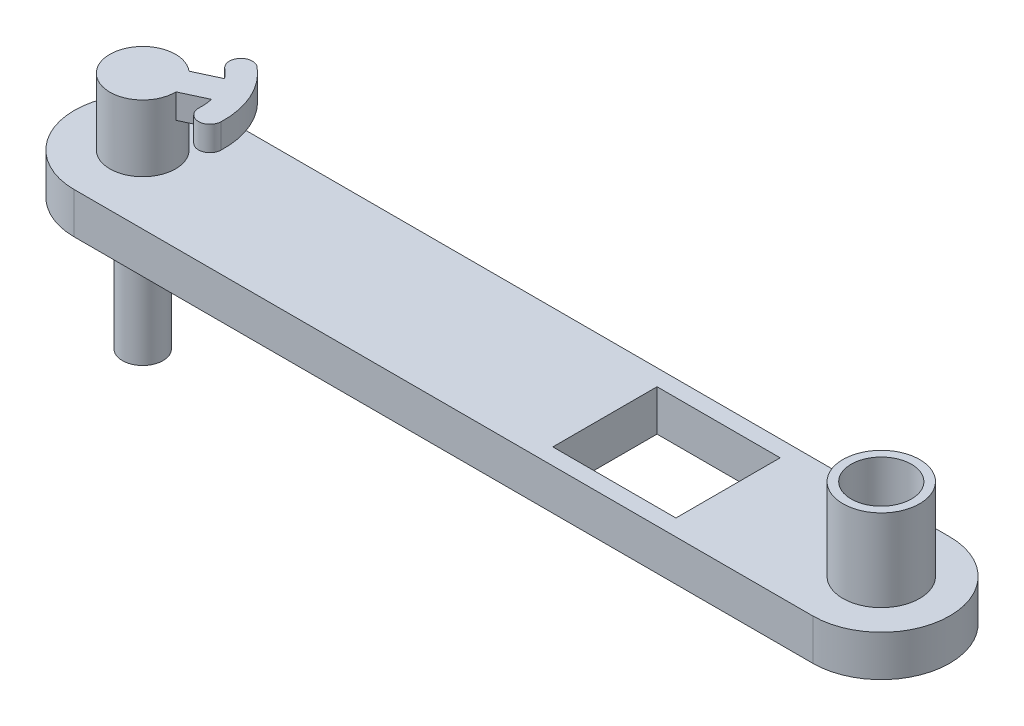
SolidWorks part; units mm, degrees
ref_plane "Front Plane" through (0, 0, 0) normal (0, 0, 1) x (1, 0, 0)
ref_plane "Top Plane" through (0, 0, 0) normal (0, 1, 0) x (1, 0, 0)
ref_plane "Right Plane" through (0, 0, 0) normal (1, 0, 0) x (0, 0, -1)
sketch "Sketch1" plane through (0, 0, 0) normal (0, 1, 0) x (1, 0, 0)
  line L0 (0, 0) -> (90, 0) construction
  line L1 (0, 8.35) -> (90, 8.35)
  line L2 (0, -8.35) -> (90, -8.35)
  arc A0 (0, 8.35) -> (0, -8.35) centre (0, 0) ccw
  arc A1 (90, -8.35) -> (90, 8.35) centre (90, 0) ccw
  point P3 (45, 0)
extrude "corps" add sketch "Sketch1" along normal blind 5
sketch "Esquisse1" plane through (0, 0, 0) normal (0, -1, 0) x (1, 0, 0)
  circle A0 centre (0, 0) radius 2.475
  dimension "D1" = 4.95
extrude "pulley hold" add sketch "Esquisse1" along normal blind 16
sketch "Esquisse2" plane through (0, 5, 0) normal (0, 1, 0) x (1, 0, 0)
  circle A0 centre (0, 0) radius 4
extrude "knob hold" add sketch "Esquisse2" along normal blind 8.1
sketch "Esquisse4" plane through (0, 5, 0) normal (0, 1, 0) x (1, 0, 0)
  line L0 (3.9996, 0.058) -> (6.9534, 1.4354)
  line L1 (2.6038, 3.0365) -> (5.5603, 4.4151)
  arc A0 (8.4947, -0.2991) -> (5.4051, 6.5601) centre (0, 0) ccw construction
  arc A2 (3.9996, 0.058) -> (2.6038, 3.0365) centre (0, 0) ccw
  arc A3 (9.8939, -0.3484) -> (6.2954, 7.6405) centre (0, 0) ccw
  arc A4 (7.0956, -0.2499) -> (6.9534, 1.4354) centre (0, 0) ccw
  arc A5 (7.0956, -0.2499) -> (9.8939, -0.3484) centre (8.4947, -0.2991) ccw
  arc A6 (6.2954, 7.6405) -> (4.5149, 5.4796) centre (5.4051, 6.5601) ccw
  arc A7 (2.6038, 3.0365) -> (3.9996, 0.058) centre (0, 0) ccw construction
  arc A8 (5.5603, 4.4151) -> (4.5149, 5.4796) centre (0, 0) ccw
  arc A9 (6.9534, 1.4354) -> (5.5603, 4.4151) centre (0, 0) ccw construction
  point P10 (7.7501, 3.4909)
  dimension "D1" = 9.9
  dimension "D2" = 2.8
extrude "knob" add sketch "Esquisse4" along normal blind 3 from offset 5.1
sketch "Esquisse3" plane through (0, 0, 0) normal (0, -1, 0) x (1, 0, 0)
  line L3 (71.325, 6.35) -> (56.325, 6.35)
  line L4 (71.325, 6.35) -> (71.325, -6.35)
  line L5 (71.325, -6.35) -> (56.325, -6.35)
  line L6 (56.325, 6.35) -> (56.325, -6.35)
  circle A2 centre (90, 0) radius 3.675
  point P7 (71.325, 0)
  dimension "D1" = 12.7
  dimension "D4" = 7.35
  dimension "D2" = 15
  dimension "D3" = 18.675
extrude "Enlèv. mat.-Extru.1" cut sketch "Esquisse3" against normal through all
sketch "Esquisse5" plane through (0, 5, 0) normal (0, 1, 0) x (1, 0, 0)
  circle A0 centre (90, 0) radius 3.675 construction
  circle A1 centre (90, 0) radius 3.675
  circle A2 centre (90, 0) radius 4.675
  dimension "D1" = 1
extrude "Boss.-Extru.1" add sketch "Esquisse5" along normal blind 10
